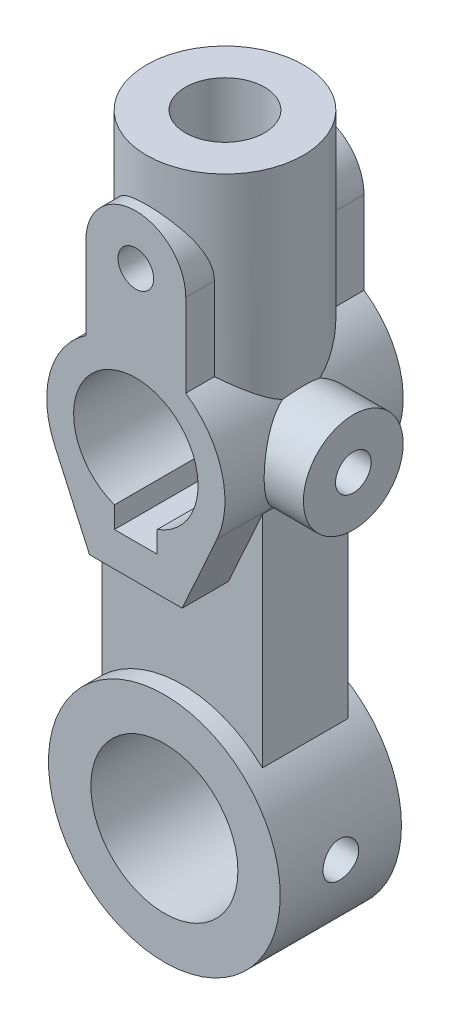
SolidWorks part; units mm, degrees
ref_plane "Alzado" through (0, 0, 0) normal (0, 0, 1) x (1, 0, 0)
ref_plane "Planta" through (0, 0, 0) normal (0, 1, 0) x (1, 0, 0)
ref_plane "Vista lateral" through (0, 0, 0) normal (1, 0, 0) x (0, 0, -1)
sketch "Croquis1" plane through (0, 0, 0) normal (0, 0, 1) x (1, 0, 0)
  circle A0 centre (0, 0) radius 32.5
  dimension "D1" = 65
extrude "Saliente-Extruir1" add sketch "Croquis1" along normal blind 34
ref_plane "Plano1" through (0, 0, 17) normal (0, 0, 1) x (1, 0, 0)
sketch "Croquis2" plane through (0, 0, 17) normal (0, 0, 1) x (1, 0, 0)
  line L0 (-22.5, 0) -> (22.5, 0)
  line L1 (22.5, 0) -> (22.5, 96)
  line L2 (22.5, 96) -> (-22.5, 96)
  line L3 (-22.5, 96) -> (-22.5, 0)
  dimension "D1" = 96
  dimension "D2" = 45
  dimension "D3" = 22.5
extrude "Saliente-Extruir3" add sketch "Croquis2" along normal blind 12 and the other way blind 12
sketch "Croquis4" plane through (0, 0, 34) normal (0, 0, 1) x (1, 0, 0)
  circle A0 centre (0, 0) radius 20.625
  dimension "D1" = 41.25
extrude "Cortar-Extruir1" cut sketch "Croquis4" against normal through all
sketch "Croquis6" plane through (0, 96, 0) normal (0, 1, 0) x (1, 0, 0)
  line L0 (-22.5, -5) -> (22.5, -29) construction
  circle A0 centre (0, -17) radius 22
  dimension "D1" = 44
extrude "Saliente-Extruir4" add sketch "Croquis6" along normal blind 70
sketch "Croquis7" plane through (0, 0, 29) normal (0, 0, 1) x (1, 0, 0)
  line L0 (0, 0) -> (0, 96) construction
  line L1 (-18.4391, 96) -> (18.4391, 96) construction
  line L2 (-13, 64) -> (13, 64)
  line L3 (-22.5, 96) -> (-22.5, 23.4521) construction
  line L4 (-13, 64) -> (-22.7923, 85.7281)
  line L5 (13, 64) -> (22.7923, 85.7281)
  line L6 (-14, 140) -> (-14, 116.7123)
  line L7 (14, 140) -> (14, 116.7123)
  arc A0 (22.7923, 85.7281) -> (14, 116.7123) centre (0, 96) ccw
  arc A1 (14, 140) -> (-14, 140) centre (0, 140) ccw
  arc A2 (-14, 116.7123) -> (-22.7923, 85.7281) centre (0, 96) ccw
  dimension "D1" = 50
  dimension "D6" = 28
  dimension "D2" = 32
  dimension "D3" = 26
  dimension "D4" = 9.5
  dimension "D5" = 44
extrude "Saliente-Extruir5" add sketch "Croquis7" along normal blind 13 and the other way blind 37
ref_plane "Plano3" through (0, 0, 0) normal (1, 0, 0) x (0, 0, -1)
sketch "Croquis9" plane through (0, 0, 0) normal (1, 0, 0) x (0, 0, -1)
  circle A0 centre (-17, 96) radius 14
  dimension "D1" = 28
  dimension "D2" = 96
extrude "Saliente-Extruir6" add sketch "Croquis9" along normal blind 36
sketch "Croquis10" plane through (0, 0, 42) normal (0, 0, 1) x (1, 0, 0)
  line L0 (-6, 73.61) -> (6, 73.61)
  line L1 (-22.5, 85.0796) -> (-22.5, 23.4521) construction
  line L2 (-6, 73.61) -> (-6, 79.614)
  line L3 (6, 73.61) -> (6, 79.614)
  arc A0 (6, 79.614) -> (-6, 79.614) centre (0, 96) ccw
  circle A1 centre (0, 140) radius 5
  dimension "D1" = 34.9
  dimension "D5" = 10
  dimension "D2" = 12
  dimension "D3" = 16.5
  dimension "D4" = 22.39
extrude "Cortar-Extruir3" cut sketch "Croquis10" against normal through all
sketch "Croquis12" plane through (0, 166, 0) normal (0, 1, 0) x (1, 0, 0)
  circle A0 centre (0, -17) radius 11.1
  dimension "D1" = 22.2
extrude "Cortar-Extruir4" cut sketch "Croquis12" against normal blind 70
sketch "Croquis13" plane through (36, 0, 0) normal (1, 0, 0) x (0, 0, -1)
  circle A0 centre (-17, 96) radius 5
  dimension "D1" = 10
extrude "Cortar-Extruir5" cut sketch "Croquis13" against normal blind 36
ref_plane "Plano4" through (0, 0, 0) normal (1, 0, 0) x (0, 0, -1)
sketch "Croquis14" plane through (0, 0, 0) normal (1, 0, 0) x (0, 0, -1)
  line L0 (0, -32.5) -> (0, 32.5) construction
  line L1 (-34, -32.5) -> (0, -32.5) construction
  circle A0 centre (-17, 0) radius 5
  dimension "D1" = 10
  dimension "D2" = 17
  dimension "D3" = 32.5
extrude "Cortar-Extruir7" cut sketch "Croquis14" along normal through all
